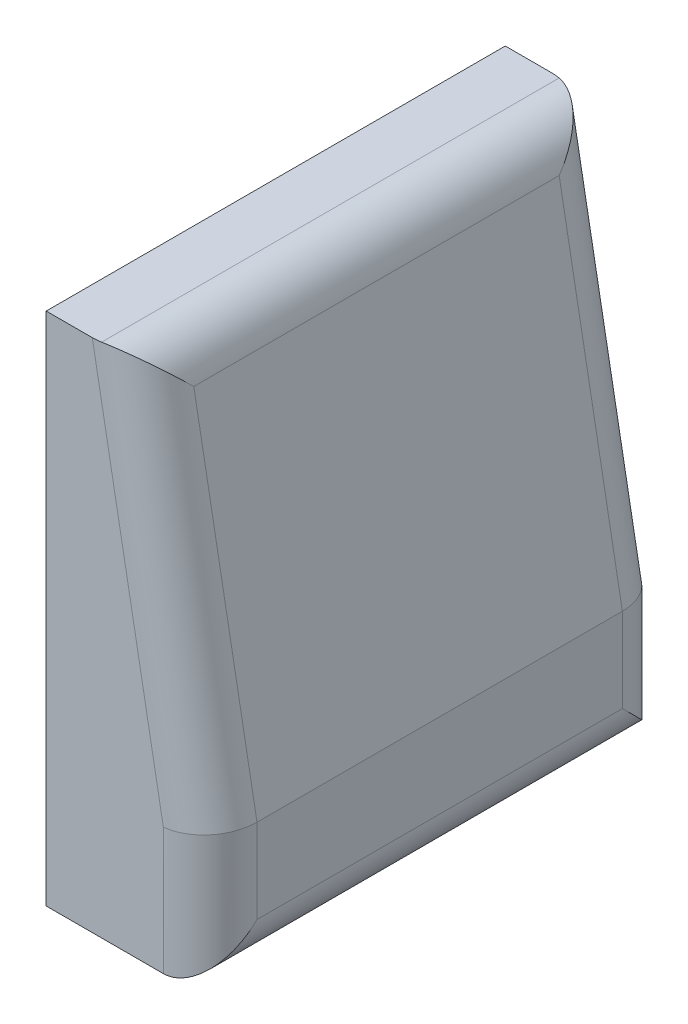
SolidWorks part; units mm, degrees
ref_plane "Front Plane" through (0, 0, 0) normal (0, 0, 1) x (1, 0, 0)
ref_plane "Top Plane" through (0, 0, 0) normal (0, 1, 0) x (1, 0, 0)
ref_plane "Right Plane" through (0, 0, 0) normal (1, 0, 0) x (0, 0, -1)
sketch "Sketch1" plane through (0, 0, 0) normal (0, 0, 1) x (1, 0, 0)
  line L0 (0, 550) -> (0, -550)
  line L1 (0, -550) -> (350, -550)
  line L2 (350, -550) -> (350, -270)
  line L3 (350, -270) -> (200, 550)
  line L4 (200, 550) -> (0, 550)
  dimension "D1" = 1100
  dimension "D2" = 200
  dimension "D3" = 350
  dimension "D4" = 280
extrude "Boss-Extrude1" add sketch "Sketch1" along normal mid plane 980
fillet "Fillet1" radius 100 6 edges at (350, -410, -490) (275, 140, -490) (350, -550, 0) (350, -410, 490) (275, 140, 490) (200, 550, 0)
